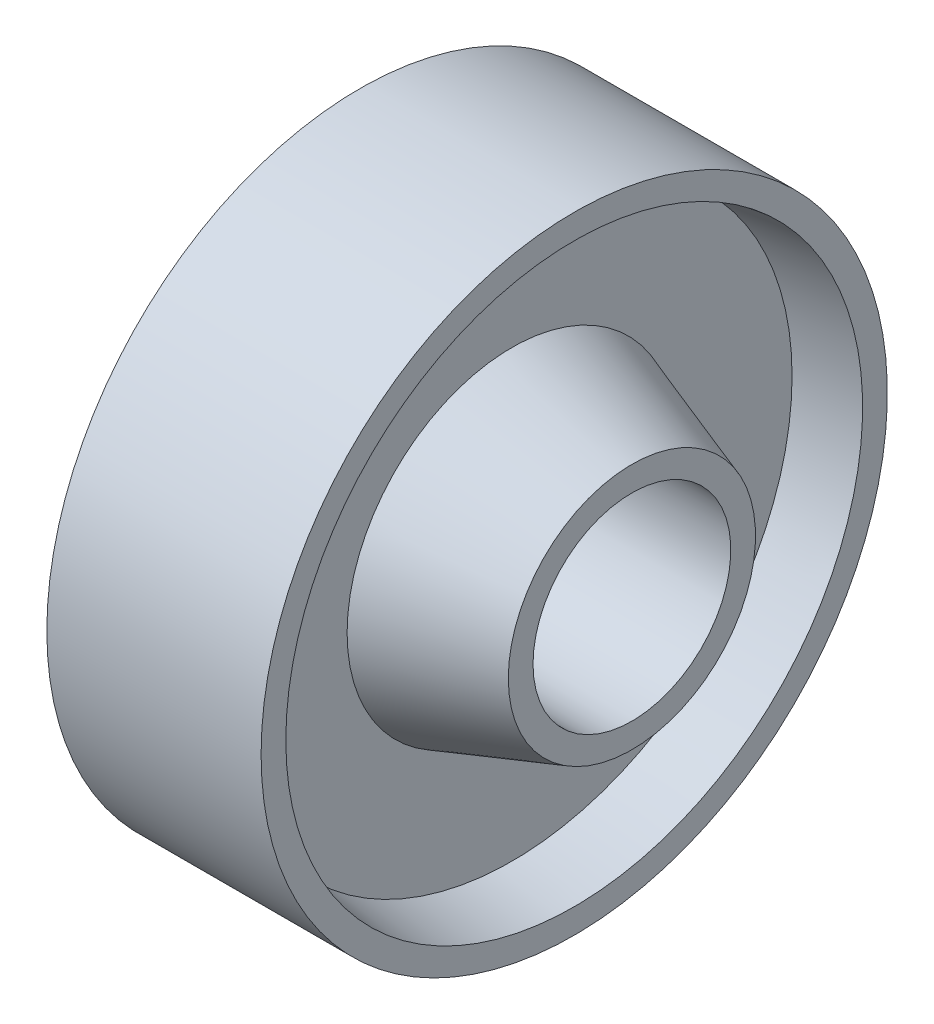
SolidWorks part; units mm, degrees
ref_plane "Front Plane" through (0, 0, 0) normal (0, 0, 1) x (1, 0, 0)
ref_plane "Top Plane" through (0, 0, 0) normal (0, 1, 0) x (1, 0, 0)
ref_plane "Right Plane" through (0, 0, 0) normal (1, 0, 0) x (0, 0, -1)
sketch "Sketch3" plane through (0, 0, 0) normal (0, 0, 1) x (1, 0, 0)
  line L0 (-39.0783, 0) -> (37.9724, 0) construction
  line L1 (-21.0138, 12) -> (18.9862, 12)
  line L2 (18.9862, 12) -> (18.9862, 15)
  line L3 (-21.0138, 12) -> (-21.0138, 15)
  line L4 (-1.0138, 12) -> (-1.0138, 47.0968) construction
  line L5 (-6.4516, 34) -> (-6.4516, 20)
  line L6 (4.424, 34) -> (4.424, 20)
  line L7 (-21.0138, 15) -> (-6.4516, 20)
  line L8 (18.9862, 15) -> (4.424, 20)
  line L9 (-14.0138, 38) -> (11.9862, 38)
  line L10 (-14.0138, 38) -> (-14.0138, 35)
  line L11 (11.9862, 38) -> (11.9862, 35)
  line L12 (-6.4516, 34) -> (-14.0138, 35)
  line L13 (4.424, 34) -> (11.9862, 35)
  dimension "D1" = 40
  dimension "D2" = 3
  dimension "D3" = 5
  dimension "D4" = 5
  dimension "D5" = 14
  dimension "D6" = 26
  dimension "D7" = 13
  dimension "D8" = 38
  dimension "D9" = 3
  dimension "D10" = 12
revolve "Revolve1" add sketch "Sketch3" angle 360 about L0
